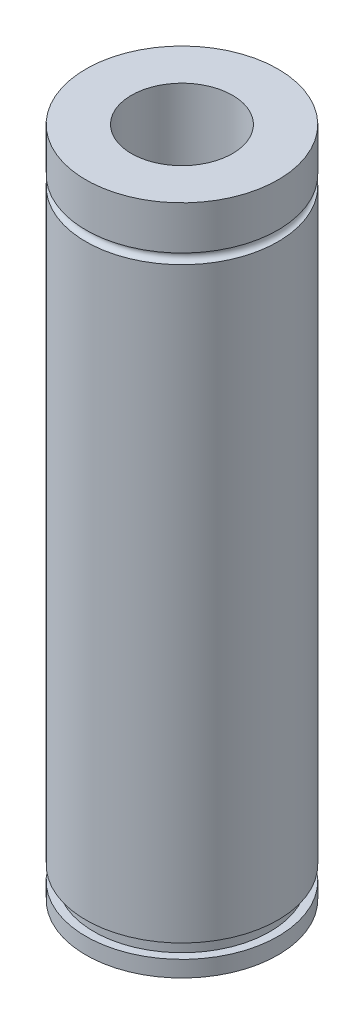
SolidWorks part; units mm, degrees
ref_plane "Front Plane" through (0, 0, 0) normal (0, 0, 1) x (1, 0, 0)
ref_plane "Top Plane" through (0, 0, 0) normal (0, 1, 0) x (1, 0, 0)
ref_plane "Right Plane" through (0, 0, 0) normal (1, 0, 0) x (0, 0, -1)
sketch "Sketch1" plane through (0, 0, 0) normal (0, 0, 1) x (1, 0, 0)
  line L0 (0, 0) -> (47.5, 0)
  line L1 (47.5, 0) -> (47.5, 8)
  line L2 (47.5, 8) -> (43.5, 8)
  line L3 (43.5, 8) -> (43.5, 15)
  line L4 (43.5, 15) -> (47.5, 15)
  line L5 (47.5, 15) -> (47.5, 305.5)
  line L6 (47.5, 332) -> (25, 332)
  line L7 (25, 332) -> (25, 82)
  line L8 (25, 82) -> (0, 82)
  line L9 (0, 82) -> (0, 0)
  line L10 (0, 0) -> (0, 458.8883) construction
  line L11 (47.5, 310.5) -> (47.5, 332)
  arc A0 (47.5, 310.5) -> (47.5, 305.5) centre (47.5, 308) ccw
  dimension "D9" = 2.5
  dimension "D1" = 95
  dimension "D2" = 8
  dimension "D3" = 87
  dimension "D4" = 7
  dimension "D5" = 317
  dimension "D6" = 50
  dimension "D7" = 250
  dimension "D8" = 24
revolve "Revolve1" add sketch "Sketch1" angle 360 about L10
